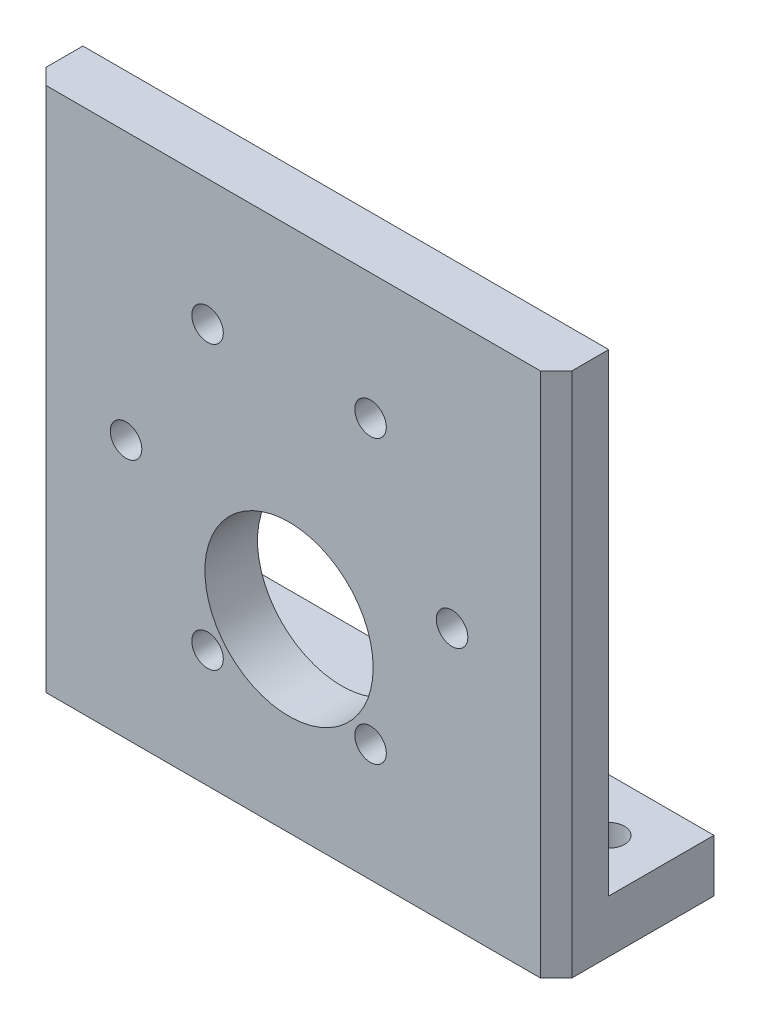
SolidWorks part; units mm, degrees
ref_plane "Front Plane" through (0, 0, 0) normal (0, 0, 1) x (1, 0, 0)
ref_plane "Top Plane" through (0, 0, 0) normal (0, 1, 0) x (1, 0, 0)
ref_plane "Right Plane" through (0, 0, 0) normal (1, 0, 0) x (0, 0, -1)
sketch "Sketch2" plane through (0, 0, 0) normal (0, 0, 1) x (1, 0, 0)
  line L4 (-24.3883, -24.288) -> (25.6117, -24.288)
  line L5 (-24.3883, -24.288) -> (-24.3883, 25.712)
  line L6 (-24.3883, 25.712) -> (25.6117, 25.712)
  line L7 (25.6117, -24.288) -> (25.6117, 25.712)
  line L8 (-24.3883, -24.288) -> (25.6117, 25.712) construction
  line L9 (-24.3883, 25.712) -> (25.6117, -24.288) construction
  circle A6 centre (0.2117, -6.688) radius 8
  circle A7 centre (-7.5383, 13.7353) radius 1.5
  circle A8 centre (7.9617, 13.7353) radius 1.5
  circle A9 centre (-15.2883, 0.312) radius 1.5
  circle A10 centre (-7.5383, -13.1114) radius 1.5
  circle A11 centre (7.9617, -13.1114) radius 1.5
  circle A12 centre (15.7117, 0.312) radius 1.5
  point P0 (0.6117, 0.712)
  dimension "D3" = 16
  dimension "D1" = 50
  dimension "D2" = 50
extrude "Boss-Extrude1" add sketch "Sketch2" along normal blind 5
sketch "Sketch5" plane through (0, 0, 0) normal (0, 0, -1) x (-1, 0, 0)
  line L0 (24.3883, 25.712) -> (24.3883, -24.288) construction
  line L1 (-25.6117, -24.288) -> (24.3883, -24.288)
  line L2 (-25.6117, -24.288) -> (-25.6117, -19.288)
  line L3 (-25.6117, -19.288) -> (24.3883, -19.288)
  line L4 (24.3883, -24.288) -> (24.3883, -19.288)
  dimension "D1" = 5
extrude "Boss-Extrude2" add sketch "Sketch5" along normal blind 10
sketch "Sketch6" plane through (0, -24.288, 0) normal (0, -1, 0) x (1, 0, 0)
  line L0 (25.6117, -10) -> (-24.3883, -10) construction
  line L1 (0.6117, 5) -> (0.6117, -10) construction
  line L2 (-24.3883, 5) -> (25.6117, 5) construction
  circle A0 centre (-19.3883, -5) radius 1.5
  circle A1 centre (20.6117, -5) radius 1.5
  dimension "D3" = 3
  dimension "D4" = 3
  dimension "D1" = 5
  dimension "D2" = 5
  dimension "D5" = 20
  dimension "D6" = 20
extrude "Cut-Extrude2" cut sketch "Sketch6" against normal blind 10
chamfer "Chamfer1" distance 1.5 angle 45 2 edges at (25.6117, 0.712, 5) (-24.3883, 0.712, 5)
